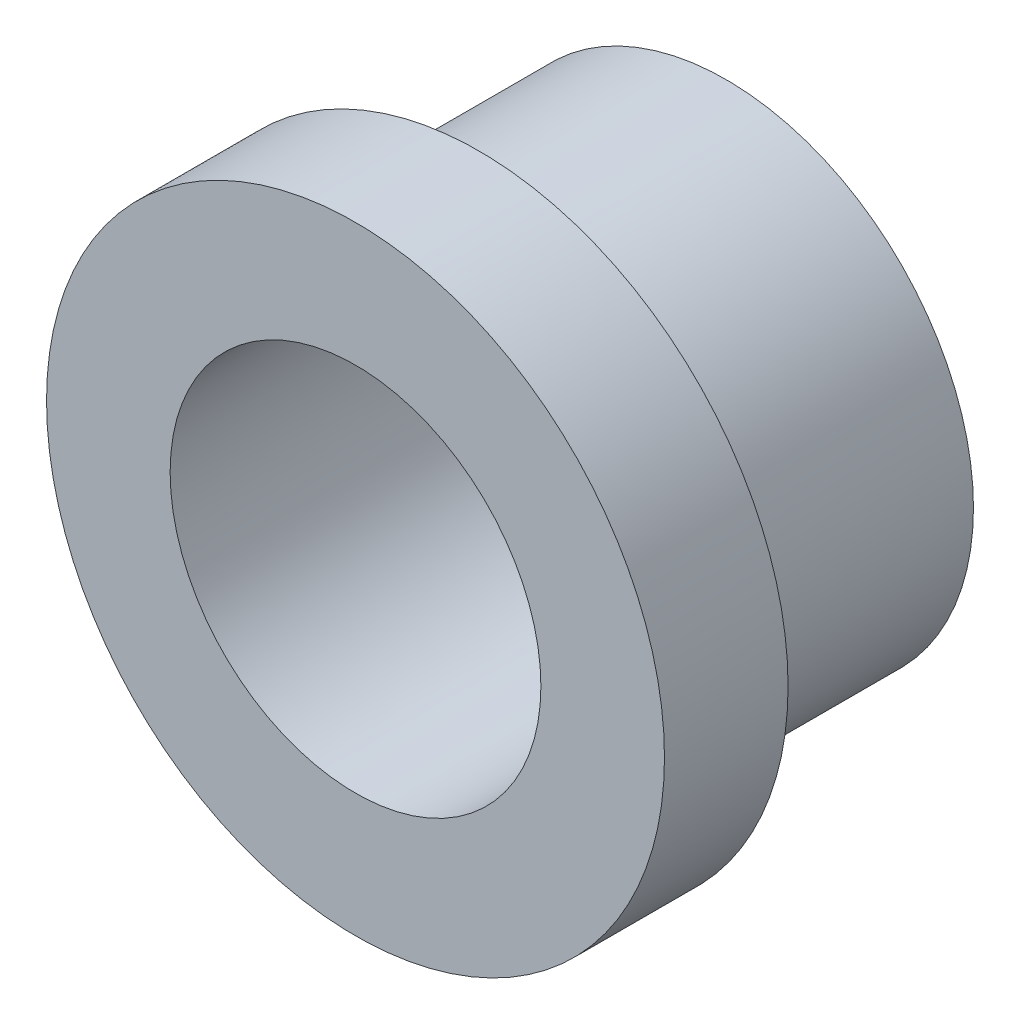
SolidWorks part; units mm, degrees
ref_plane "Front Plane" through (0, 0, 0) normal (0, 0, 1) x (1, 0, 0)
ref_plane "Top Plane" through (0, 0, 0) normal (0, 1, 0) x (1, 0, 0)
ref_plane "Right Plane" through (0, 0, 0) normal (1, 0, 0) x (0, 0, -1)
sketch "Sketch1" plane through (0, 0, 0) normal (0, 0, 1) x (1, 0, 0)
  circle A0 centre (0, 0) radius 6.35
  circle A1 centre (0, 0) radius 4.7625
  dimension "D1" = 12.7
  dimension "D2" = 9.525
extrude "Boss-Extrude1" add sketch "Sketch1" along normal blind 6.35
sketch "Sketch2" plane through (0, 0, 6.35) normal (0, 0, 1) x (1, 0, 0)
  circle A0 centre (0, 0) radius 7.9375
  circle A1 centre (0, 0) radius 4.7625
  circle A2 centre (0, 0) radius 4.7625 construction
  dimension "D1" = 15.875
extrude "Boss-Extrude2" add sketch "Sketch2" along normal blind 3.175
